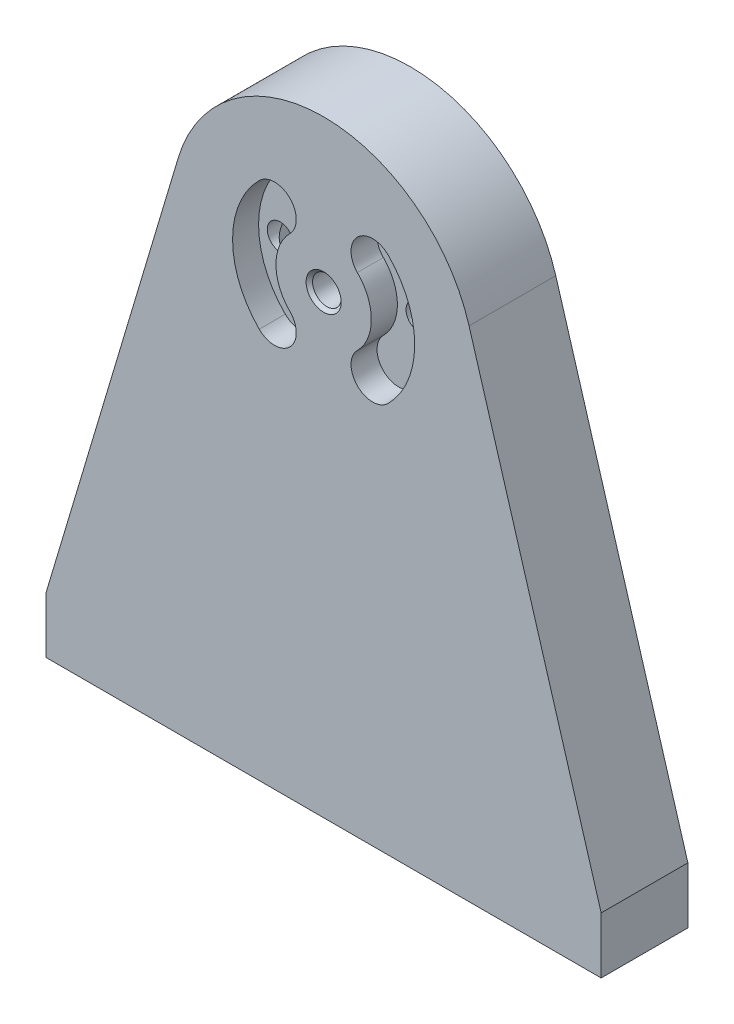
SolidWorks part; units mm, degrees
ref_plane "Ön Düzlem" through (0, 0, 0) normal (0, 0, 1) x (1, 0, 0)
ref_plane "Üst Düzlem" through (0, 0, 0) normal (0, 1, 0) x (1, 0, 0)
ref_plane "Sağ Düzlem" through (0, 0, 0) normal (1, 0, 0) x (0, 0, -1)
sketch "Çizim2" plane through (0, 0, 0) normal (0, 0, 1) x (1, 0, 0)
  line L0 (-32, 0) -> (32, 0)
  line L1 (32, 0) -> (32, 6.5)
  line L2 (-32, 0) -> (-32, 6.5)
  line L3 (0, 0) -> (0, 72.4922) construction
  line L4 (0, 52.5) -> (10.6027, 63.1027) construction
  line L5 (-5.6569, 58.1569) -> (0, 52.5) construction
  line L6 (-32, 6.5) -> (-16.7683, 57.5073)
  line L7 (32, 6.5) -> (16.7683, 57.5073)
  line L8 (-5.6569, 46.8431) -> (0, 52.5)
  arc A1 (16.7683, 57.5073) -> (-16.7683, 57.5073) centre (0, 52.5) ccw
  circle A4 centre (0, 52.5) radius 8 construction
  arc A20 (-5.6569, 58.1569) -> (-5.6569, 46.8431) centre (0, 52.5) ccw construction
  arc A21 (-7.4246, 59.9246) -> (-7.4246, 45.0754) centre (0, 52.5) ccw
  arc A22 (-3.8891, 56.3891) -> (-3.8891, 48.6109) centre (0, 52.5) ccw
  arc A23 (-3.8891, 56.3891) -> (-7.4246, 59.9246) centre (-5.6569, 58.1569) ccw
  arc A24 (-7.4246, 45.0754) -> (-3.8891, 48.6109) centre (-5.6569, 46.8431) ccw
  arc A25 (5.6569, 58.1569) -> (5.6569, 46.8431) centre (0, 52.5) cw construction
  arc A26 (7.4246, 59.9246) -> (7.4246, 45.0754) centre (0, 52.5) cw
  arc A27 (3.8891, 56.3891) -> (3.8891, 48.6109) centre (0, 52.5) cw
  arc A28 (3.8891, 56.3891) -> (7.4246, 59.9246) centre (5.6569, 58.1569) cw
  arc A29 (7.4246, 45.0754) -> (3.8891, 48.6109) centre (5.6569, 46.8431) cw
  point P4 (0, 0)
  point P16 (-8, 52.5)
  point P17 (0, 52.5)
  point P25 (8, 52.5)
  dimension "D1" = 52.5
  dimension "D4" = 35
  dimension "D5" = 16
  dimension "D6" = 45
  dimension "D8" = 2.5
  dimension "D9" = 45
  dimension "D2" = 64
  dimension "D3" = 6.5
  dimension "D10" = 45
extrude "Yükseklik-Ekstrüzyon1" add sketch "Çizim2" along normal mid plane 10
hole_wizard "M4 Dişli Delik1" positions "Çizim7" profile "Çizim8" tap size "M4" standard "ISO" end condition through all
sketch "Çizim7" plane through (0, 0, 5) normal (0, 0, 1) x (1, 0, 0)
  point P0 (0, 52.5)
sketch "Çizim8" plane through (0, 52.5, 5) normal (1, 0, 0) x (0, -1, 0)
  line L0 (0, 0) -> (0, 10)
  line L1 (0, 10) -> (1.65, 10)
  line L2 (1.65, 10) -> (1.65, 0.375)
  line L3 (1.65, 0.375) -> (2.025, 0)
  line L5 (2.025, 0) -> (0, 0)
  line L6 (-1.65, 0.375) -> (-2.025, 0) construction
  line L11 (0, -6.35) -> (0, 107.95) construction
  dimension "Thru Tap Drill Dia." = 3.3
  dimension "Thru Tap Drill Depth" = 10
  dimension "Near C'Sink Dia." = 4.05
  dimension "Near C'Sink Angle" = 90
cosmetic thread "Delik Dişi1" parameters "D2"=4
sketch "Çizim9" plane through (0, 0, 0) normal (0, -1, 0) x (1, 0, 0)
  line L0 (0, 0) -> (-22, 0) construction
  line L1 (70.6512, 0) -> (-70.6512, 0) construction
  line L2 (0, 0) -> (22, 0) construction
  dimension "D1" = 22
  dimension "D2" = 22
hole_wizard "M4 Dişli Delik2" positions "Çizim10" profile "Çizim11" tap size "M4" standard "ISO"
sketch "Çizim10" plane through (0, 0, 0) normal (0, -1, 0) x (-1, 0, 0)
  point P0 (22, 0)
  point P3 (-22, 0)
sketch "Çizim11" plane through (-22, 0, 0) normal (1, 0, 0) x (0, 0, -1)
  line L0 (0, 0) -> (0, 12.9914)
  line L1 (0, 12.9914) -> (1.65, 12)
  line L2 (1.65, 12) -> (1.65, 0.375)
  line L3 (1.65, 0.375) -> (2.025, 0)
  line L5 (2.025, 0) -> (0, 0)
  line L6 (-1.65, 0.375) -> (-2.025, 0) construction
  line L10 (0, 12.9914) -> (-1.65, 12) construction
  line L11 (0, -6.35) -> (0, 107.95) construction
  dimension "Tap Drill Dia." = 3.3
  dimension "Tap Drill Depth" = 12
  dimension "Near C'Sink Dia." = 4.05
  dimension "Near C'Sink Angle" = 90
  dimension "Drill Angle" = 118
cosmetic thread "Delik Dişi2" parameters "D1"=10, "D2"=4
cosmetic thread "Delik Dişi3" parameters "D1"=10, "D2"=4
sketch "Çizim12" plane through (0, 0, 0) normal (0, -1, 0) x (1, 0, 0)
  line L0 (0, 0) -> (-22, 0) construction
  line L1 (0, 0) -> (22, 0) construction
  circle A0 centre (-8, 0) radius 1.5
  circle A1 centre (8, 0) radius 1.5
  point P8 (7.6564, 0)
  point P9 (-10.2581, 0)
  dimension "D1" = 3
  dimension "D2" = 8
  dimension "D3" = 8
extrude "Kes-Ekstrüzyon1" cut sketch "Çizim12" against normal blind 54
sketch "Çizim13" plane through (0, 0, 5) normal (0, 0, -1) x (-1, 0, 0)
  line L0 (5.6569, 58.1569) -> (0, 52.5) construction
  line L1 (0, 52.5) -> (0, 64.7537)
  line L2 (0, 52.5) -> (0, 41.1697)
  line L3 (5.6569, 46.8431) -> (0, 52.5) construction
  circle A0 centre (0, 52.5) radius 8 construction
  arc A1 (5.6569, 58.1569) -> (5.6569, 46.8431) centre (0, 52.5) cw construction
  arc A2 (7.4246, 45.0754) -> (7.4246, 59.9246) centre (0, 52.5) ccw
  arc A3 (3.8891, 48.6109) -> (3.8891, 56.3891) centre (0, 52.5) ccw
  arc A4 (3.8891, 48.6109) -> (7.4246, 45.0754) centre (5.6569, 46.8431) ccw
  arc A5 (7.4246, 59.9246) -> (3.8891, 56.3891) centre (5.6569, 58.1569) ccw
  arc A7 (-5.6569, 58.1569) -> (-5.6569, 46.8431) centre (0, 52.5) ccw construction
  arc A8 (-7.4246, 45.0754) -> (-7.4246, 59.9246) centre (0, 52.5) cw
  arc A9 (-3.8891, 48.6109) -> (-3.8891, 56.3891) centre (0, 52.5) cw
  arc A10 (-3.8891, 48.6109) -> (-7.4246, 45.0754) centre (-5.6569, 46.8431) cw
  arc A11 (-7.4246, 59.9246) -> (-3.8891, 56.3891) centre (-5.6569, 58.1569) cw
  point P5 (8, 52.5)
  point P18 (-8, 52.5)
  dimension "D1" = 16
  dimension "D2" = 2.5
  dimension "D3" = 45
  dimension "D4" = 45
extrude "Kes-Ekstrüzyon2" cut sketch "Çizim13" along normal blind 3 contours A2 A5 A3 A4 | A8 A11 A9 A10
sketch "Çizim14" plane through (0, 0, 2) normal (0, 0, 1) x (1, 0, 0)
  circle A0 centre (0, 52.5) radius 8 construction
  circle A1 centre (-8, 52.5) radius 1.5
  circle A2 centre (8, 52.5) radius 1.5
  dimension "D1" = 16
  dimension "D2" = 3
extrude "Kes-Ekstrüzyon3" cut sketch "Çizim14" against normal blind 5
